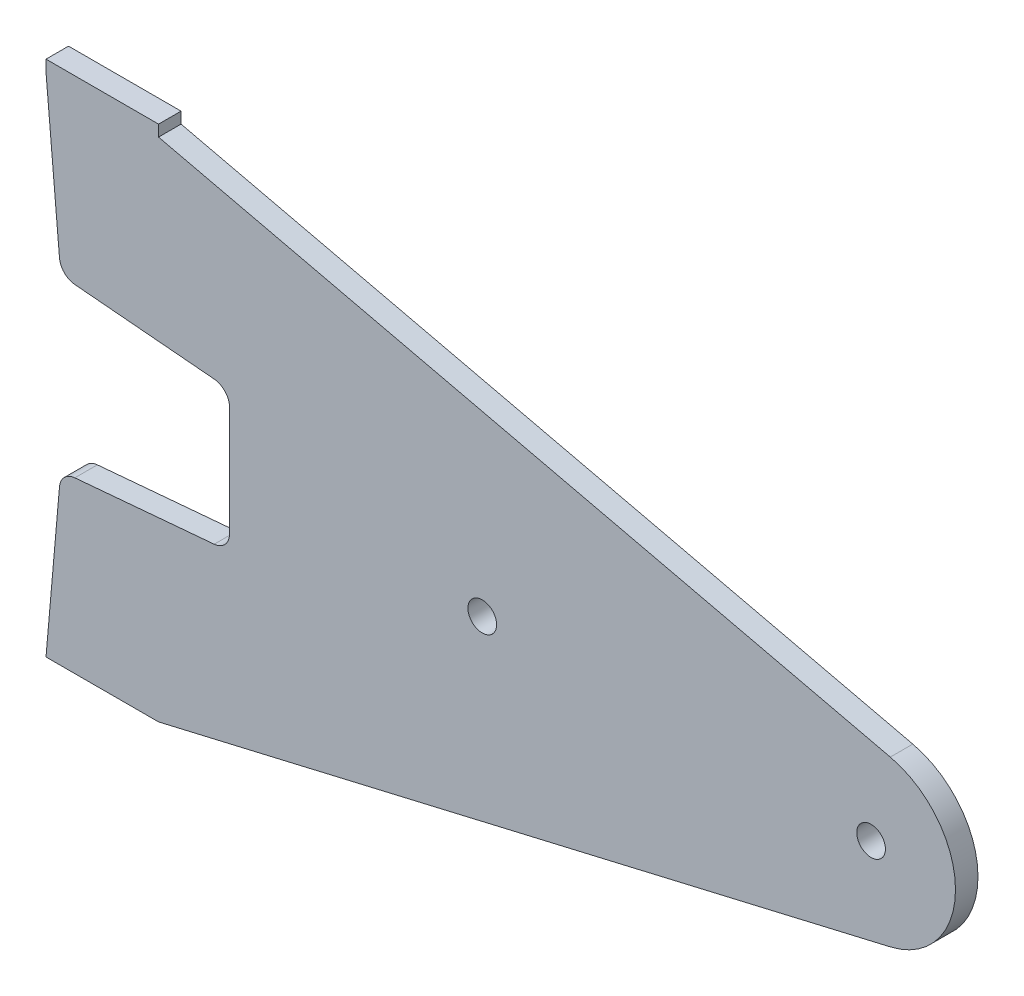
SolidWorks part; units mm, degrees
ref_plane "Front Plane" through (0, 0, 0) normal (0, 0, 1) x (1, 0, 0)
ref_plane "Top Plane" through (0, 0, 0) normal (0, 1, 0) x (1, 0, 0)
ref_plane "Right Plane" through (0, 0, 0) normal (1, 0, 0) x (0, 0, -1)
sketch "Sketch1" plane through (0, 0, 0) normal (0, 0, 1) x (1, 0, 0)
  line L0 (0, 0) -> (225, 0) construction
  line L1 (0, 0) -> (-75.9033, 0) construction
  line L2 (15, 15) -> (45, 12.375) construction
  line L3 (-45, -45) -> (45, -45) construction
  line L4 (-45, -45) -> (-45, 45) construction
  line L5 (-45, 45) -> (45, 45) construction
  line L6 (45, -45) -> (45, 45) construction
  line L7 (-45, -45) -> (45, 45) construction
  line L8 (-45, 45) -> (45, -45) construction
  line L9 (-15, -15) -> (15, -15) construction
  line L10 (-15, -15) -> (-15, 15) construction
  line L11 (-15, 15) -> (15, 15) construction
  line L12 (15, -15) -> (15, 15) construction
  line L13 (-15, -15) -> (15, 15) construction
  line L14 (-15, 15) -> (15, -15) construction
  line L15 (15, 15) -> (45, 15) construction
  line L16 (45, 45) -> (15, 15) construction
  line L17 (15, 15) -> (12.375, 45) construction
  line L18 (14.8729, 17.6) -> (12.7063, 42.3615)
  line L19 (17.6, 14.8729) -> (42.3615, 12.7063)
  line L20 (15.0923, 15.0923) -> (12.4746, 45.0087) construction
  line L21 (15.0923, 15.0923) -> (45.0087, 12.4746) construction
  line L22 (45.1, -9.7177) -> (45.1, 9.7177)
  line L23 (12.7063, 42.3615) -> (12.4746, 45.0087)
  line L24 (45.1, -45) -> (45.1, 45) construction
  line L25 (32.4746, -45) -> (12.4746, -45.0087)
  line L26 (17.6, -14.8729) -> (42.3615, -12.7063)
  line L27 (14.8729, -17.6) -> (12.7063, -42.3615) construction
  line L28 (0, -45.1) -> (9.7177, -45.1) construction
  line L29 (0, 0) -> (0, 45.1) construction
  line L30 (-14.8729, 17.6) -> (-12.7063, 42.3615) construction
  line L31 (32.4746, 45) -> (162.5092, 14.6063)
  line L32 (-45, 47) -> (45, 47) construction
  line L33 (-12.7063, 42.3615) -> (-13.7896, 29.9807) construction
  line L34 (225, -45) -> (45, -45) construction
  line L35 (225, -45) -> (225, 45) construction
  line L36 (225, 45) -> (45, 45) construction
  line L37 (45, -45) -> (45, 45) construction
  line L38 (225, -45) -> (45, 45) construction
  line L39 (225, 45) -> (45, -45) construction
  line L40 (12.4746, 45.0087) -> (12.4746, 47)
  line L41 (12.4746, 47) -> (32.4746, 47)
  line L44 (14.8729, -17.6) -> (12.7063, -42.3615)
  line L46 (12.7063, -42.3615) -> (12.4746, -45.0087)
  line L47 (32.4746, 47) -> (32.4746, 45)
  line L48 (32.4746, -45) -> (162.5092, -14.6063)
  line L49 (174.0952, 0) -> (45.1, 0) construction
  arc A0 (14.8729, 17.6) -> (17.6, 14.8729) centre (17.8615, 17.8615) ccw
  arc A1 (42.3615, 12.7063) -> (45.1, 9.7177) centre (42.1, 9.7177) cw
  arc A2 (162.5092, 14.6063) -> (162.5092, -14.6063) centre (159.0952, 0) cw
  arc A3 (42.3615, -12.7063) -> (45.1, -9.7177) centre (42.1, -9.7177) ccw
  arc A4 (14.8729, -17.6) -> (17.6, -14.8729) centre (17.8615, -17.8615) cw
  arc A5 (12.7063, -42.3615) -> (9.7177, -45.1) centre (9.7177, -42.1) cw construction
  arc A6 (-12.7063, 42.3615) -> (-9.7177, 45.1) centre (-9.7177, 42.1) cw construction
  circle A7 centre (159.0952, 0) radius 2.55
  circle A8 centre (90, 0) radius 2.55
  point P28 (135, 0)
  point P33 (45.1, 0)
  dimension "D5" = 3
  dimension "D7" = 3
  dimension "D9" = 2
  dimension "D10" = 20
  dimension "D11" = 15
  dimension "D12" = 5.1
  dimension "D13" = 90
  dimension "D1" = 90
  dimension "D2" = 0.1
  dimension "D3" = 30
  dimension "D4" = 2.625
  dimension "D8" = 180
  dimension "D6" = 0.1
extrude "Boss-Extrude1" add sketch "Sketch1" along normal blind 4
